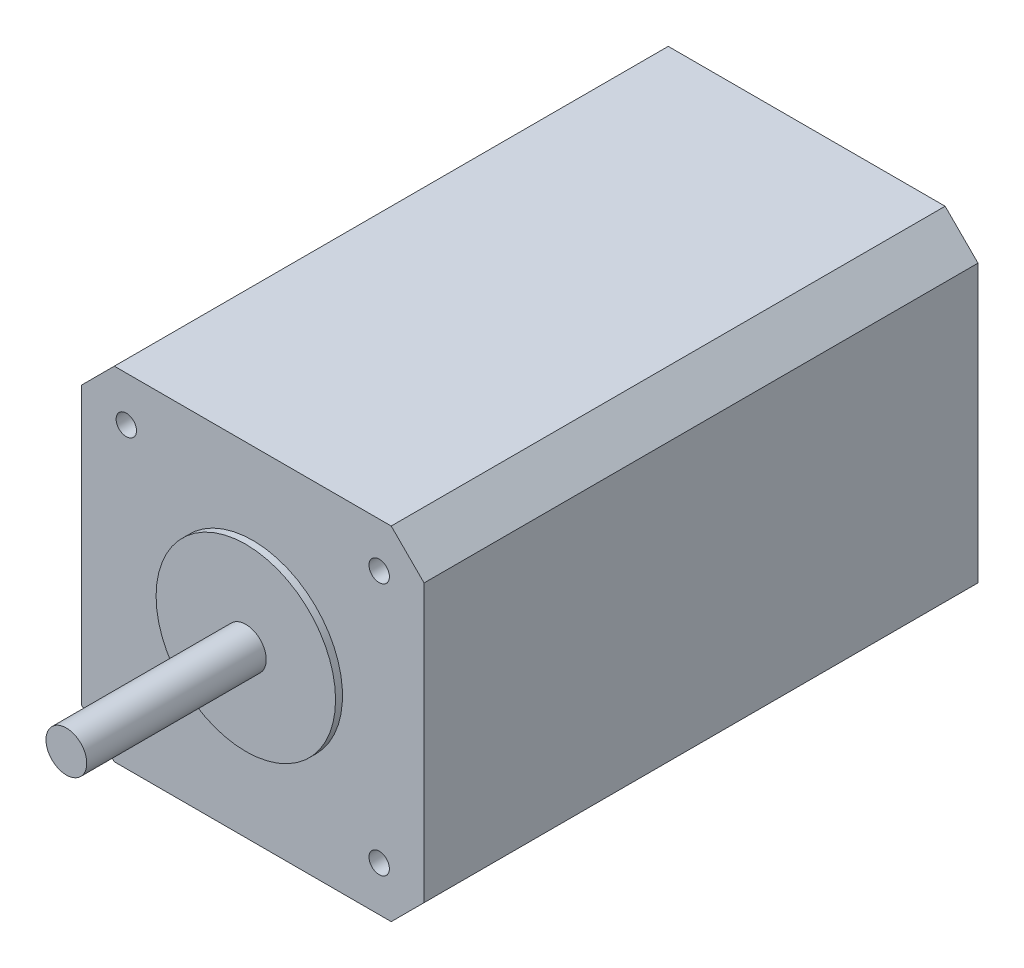
SolidWorks part; units mm, degrees
ref_plane "Front Plane" through (0, 0, 0) normal (0, 0, 1) x (1, 0, 0)
ref_plane "Top Plane" through (0, 0, 0) normal (0, 1, 0) x (1, 0, 0)
ref_plane "Right Plane" through (0, 0, 0) normal (1, 0, 0) x (0, 0, -1)
sketch "Sketch1" plane through (0, 0, 0) normal (0, 0, 1) x (1, 0, 0)
  line L1 (-21, -21) -> (21, -21)
  line L2 (-21, -21) -> (-21, 21)
  line L3 (-21, 21) -> (21, 21)
  line L4 (21, -21) -> (21, 21)
  line L5 (-21, -21) -> (21, 21) construction
  line L6 (-21, 21) -> (21, -21) construction
  point P0 (0, 0)
  dimension "D1" = 42
extrude "Boss-Extrude1" add sketch "Sketch1" along normal mid plane 67.9
sketch "Sketch2" plane through (0, 0, 33.95) normal (0, 0, 1) x (1, 0, 0)
  circle A0 centre (0, 0) radius 11
  dimension "D1" = 22
extrude "Boss-Extrude2" add sketch "Sketch2" along normal mid plane 1.7
sketch "Sketch3" plane through (0, 0, 34.8) normal (0, 0, 1) x (1, 0, 0)
  circle A0 centre (0, 0) radius 2.5
  dimension "D1" = 5
extrude "Boss-Extrude3" add sketch "Sketch3" along normal blind 22
sketch "Sketch4" plane through (0, 0, 33.95) normal (0, 0, 1) x (1, 0, 0)
  line L1 (0, -37.9716) -> (-37.9716, 0)
  line L2 (0, -37.9716) -> (37.9716, 0)
  line L3 (37.9716, 0) -> (0, 37.9716)
  line L4 (-37.9716, 0) -> (0, 37.9716)
  line L5 (0, -37.9716) -> (0, 37.9716) construction
  line L6 (37.9716, 0) -> (-37.9716, 0) construction
  line L7 (-21, -21) -> (21, -21) construction
  point P0 (0, 0)
  dimension "D1" = 45
  dimension "D2" = 53.7
extrude "Cut-Extrude-Thin1" cut sketch "Sketch4" against normal through all thin thin type one direction wall 10
hole_wizard "M3 Tapped Hole1" positions "Sketch6" profile "Sketch7" tap size "M3" standard "ISO"
sketch "Sketch6" plane through (0, 0, 33.95) normal (0, 0, 1) x (1, 0, 0)
  line L1 (15.5, -15.5) -> (-15.5, -15.5) construction
  line L2 (15.5, -15.5) -> (15.5, 15.5) construction
  line L3 (15.5, 15.5) -> (-15.5, 15.5) construction
  line L4 (-15.5, -15.5) -> (-15.5, 15.5) construction
  line L5 (15.5, -15.5) -> (-15.5, 15.5) construction
  line L6 (15.5, 15.5) -> (-15.5, -15.5) construction
  point P0 (-15.5, 15.5)
  point P69 (15.5, -15.5)
  point P70 (15.5, 15.5)
  point P71 (-15.5, -15.5)
  dimension "D1" = 31
  dimension "D2" = 15.5
  dimension "D3" = 15.5
sketch "Sketch7" plane through (-15.5, 15.5, 33.95) normal (1, 0, 0) x (0, -1, 0)
  line L0 (0, 0) -> (0, 5)
  line L1 (0, 5) -> (1.25, 4.2489)
  line L2 (1.25, 4.2489) -> (1.25, 0)
  line L5 (1.25, 0) -> (0, 0)
  line L10 (0, 5) -> (-1.25, 4.2489) construction
  line L11 (0, -6.35) -> (0, 107.95) construction
  dimension "Tap Drill Dia." = 2.5
  dimension "Tap Drill Depth" = 5
  dimension "Drill Angle" = 118
cosmetic thread "Hole Thread1" parameters "D1"=4, "D2"=3
cosmetic thread "Hole Thread2" parameters "D1"=4, "D2"=3
cosmetic thread "Hole Thread3" parameters "D1"=4, "D2"=3
cosmetic thread "Hole Thread4" parameters "D1"=4, "D2"=3
